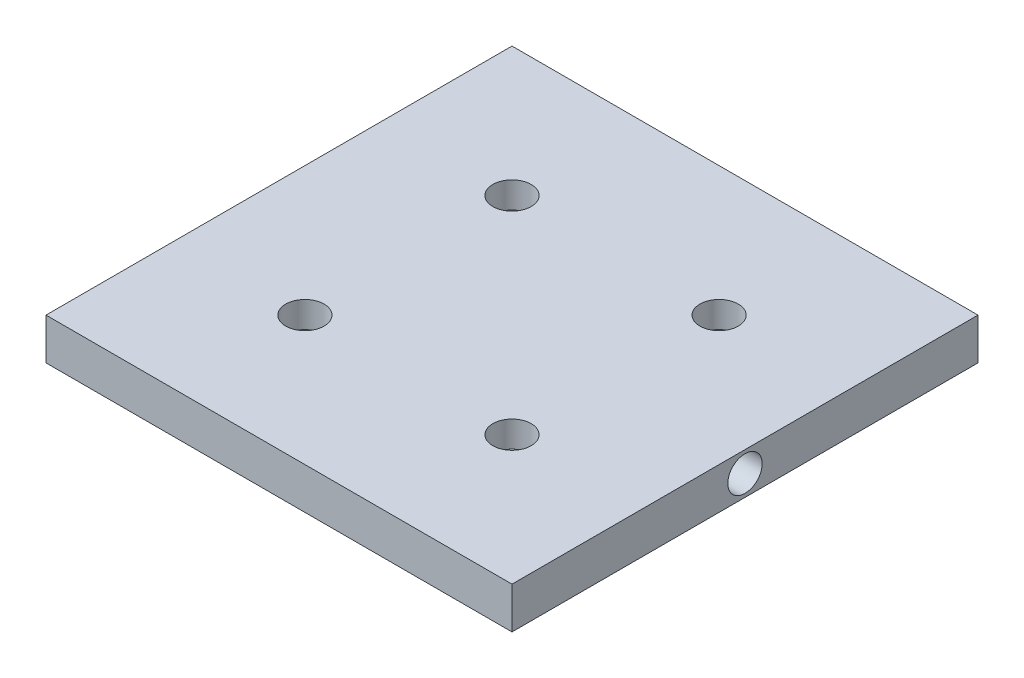
SolidWorks part; units mm, degrees
ref_plane "Front Plane" through (0, 0, 0) normal (0, 0, 1) x (1, 0, 0)
ref_plane "Top Plane" through (0, 0, 0) normal (0, 1, 0) x (1, 0, 0)
ref_plane "Right Plane" through (0, 0, 0) normal (1, 0, 0) x (0, 0, -1)
sketch "Sketch1" plane through (0, 0, 0) normal (0, 1, 0) x (1, 0, 0)
  line L1 (-57.15, 57.15) -> (57.15, 57.15)
  line L2 (-57.15, 57.15) -> (-57.15, -57.15)
  line L3 (-57.15, -57.15) -> (57.15, -57.15)
  line L4 (57.15, 57.15) -> (57.15, -57.15)
  point P4 (0, 57.15)
  point P5 (57.15, 0)
  dimension "D1" = 114.3
  dimension "D2" = 114.3
  dimension "D3" = 57.15
  dimension "D4" = 57.15
extrude "Boss-Extrude1" add sketch "Sketch1" along normal blind 10.16
hole_wizard "CBORE for M6 SHCS1" positions "Sketch2" profile "Sketch3" counterbore size "M6" standard "ANSI Metric" end condition through all
sketch "Sketch2" plane through (0, 10.16, 0) normal (0, 1, 0) x (1, 0, 0)
  line L0 (57.15, 57.15) -> (-57.15, 57.15) construction
  line L1 (-57.15, 57.15) -> (-57.15, -57.15) construction
  line L2 (57.15, -57.15) -> (57.15, 57.15) construction
  line L3 (-57.15, -57.15) -> (57.15, -57.15) construction
  point P0 (-25.4, 25.4)
  point P2 (25.4, 25.4)
  point P4 (25.4, -25.4)
  point P6 (-25.4, -25.4)
  dimension "D1" = 50.8
  dimension "D2" = 50.8
  dimension "D3" = 50.8
  dimension "D4" = 50.8
  dimension "D5" = 31.75
  dimension "D6" = 31.75
  dimension "D7" = 31.75
  dimension "D8" = 31.75
sketch "Sketch3" plane through (-25.4, 10.16, -25.4) normal (1, 0, 0) x (0, 0, 1)
  line L0 (0, 0) -> (0, 10.16)
  line L1 (0, 10.16) -> (3.3, 10.16)
  line L3 (3.3, 10.16) -> (3.3, 6.4)
  line L4 (3.3, 6.4) -> (4.7, 6.4)
  line L5 (4.7, 6.4) -> (4.7, 0)
  line L7 (4.7, 0) -> (0, 0)
  line L11 (0, -6.35) -> (0, 107.95) construction
  dimension "Thru Hole Dia." = 6.6
  dimension "Thru Hole Depth" = 10.16
  dimension "C'Bore Dia." = 9.4
  dimension "C'Bore Depth" = 6.4
sketch "Sketch6" plane through (57.15, 0, 0) normal (1, 0, 0) x (0, 0, -1)
  line L0 (-57.15, 10.16) -> (57.15, 10.16) construction
  line L1 (-57.15, 10.16) -> (-57.15, 0) construction
  circle A0 centre (0, 5.08) radius 4.2164
  dimension "D1" = 5.08
  dimension "D2" = 57.15
extrude "Cut-Extrude1" cut sketch "Sketch6" against normal blind 13.97
